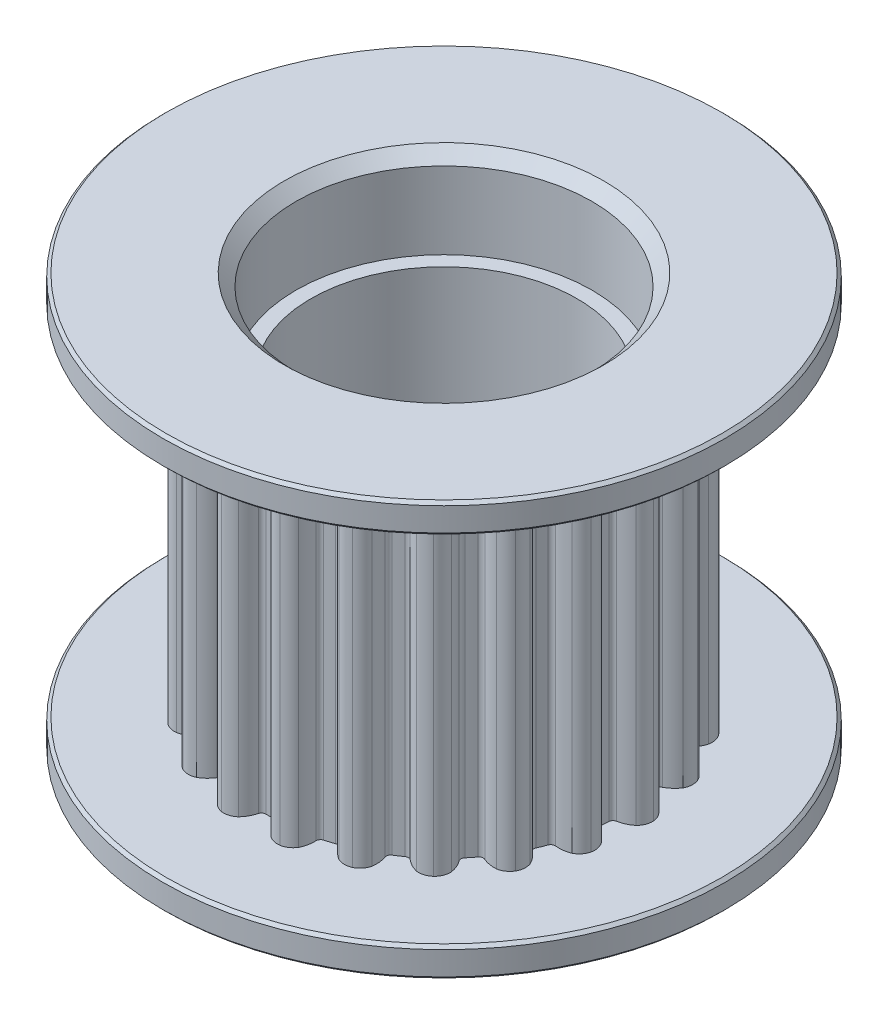
SolidWorks part; units mm, degrees
material "6061 Alloy"
ref_plane "Front Plane" through (0, 0, 0) normal (0, 0, 1) x (1, 0, 0)
ref_plane "Top Plane" through (0, 0, 0) normal (0, 1, 0) x (1, 0, 0)
ref_plane "Right Plane" through (0, 0, 0) normal (1, 0, 0) x (0, 0, -1)
sketch "Body Sketch" plane through (0, 0, 0) normal (0, 0, 1) x (1, 0, 0)
  line L0 (6.61, -6) -> (6.61, 6)
  line L1 (6.61, 6) -> (9.5, 6)
  line L2 (9.5, 6) -> (9.5, 7)
  line L3 (9.5, 7) -> (5, 7)
  line L4 (5, 7) -> (5, 4)
  line L5 (5, 4) -> (4.5, 4)
  line L6 (4.5, 4) -> (4.5, -4)
  line L7 (4.5, -4) -> (5, -4)
  line L8 (5, -4) -> (5, -7)
  line L9 (5, -7) -> (9.5, -7)
  line L10 (9.5, -7) -> (9.5, -6)
  line L11 (9.5, -6) -> (6.61, -6)
  line L12 (0, 0) -> (4.5, 0) construction
  line L13 (0, 7) -> (0, -7) construction
  dimension "BearingOD" = 10
  dimension "Height" = 14
  dimension "FlangeHeight" = 1
  dimension "BearingHeight" = 3
  dimension "BearingRestDiaControl" = 0.5
  dimension "RefBodyInnerDiameter" = 9
  dimension "FlangeDiaControl" = 4.5
  dimension "RefFlangeDia" = 19
  dimension "BeltPathDiaControl" = 1.61
  dimension "RefBeltPathDia" = 13.22
revolve "Body" add sketch "Body Sketch" angle 360 about L13
sketch "GT2 Profile Sketch" plane through (0, 0, 0) normal (0, 1, 0) x (1, 0, 0)
  line L1 (0, -6.61) -> (0, -5.86) construction
  line L2 (-0.9962, -6.5345) -> (-0.8832, -5.7931) construction
  line L3 (0, 0) -> (-0.8832, -5.7931) construction
  line L4 (0.9962, -6.5345) -> (0, 0) construction
  arc A3 (0.3083, -5.9702) -> (0.159, -5.8578) centre (0.1631, -6.0078) ccw
  arc A4 (-0.9962, -6.5345) -> (0.9962, -6.5345) centre (0, 0) ccw
  arc A5 (-0.3083, -5.9702) -> (-0.159, -5.8578) centre (-0.1631, -6.0078) cw
  arc A6 (-0.3083, -5.9702) -> (-0.5467, -6.4032) centre (-1.2763, -5.7193) cw
  circle A7 centre (0, 0) radius 6.61 construction
  arc A8 (-0.159, -5.8578) -> (0.159, -5.8578) centre (0, 0) ccw
  arc A9 (-0.5467, -6.4032) -> (-0.9962, -6.5345) centre (-0.9125, -5.9858) cw
  arc A10 (0.3083, -5.9702) -> (0.5467, -6.4032) centre (1.2763, -5.7193) ccw
  arc A11 (0.5467, -6.4032) -> (0.9962, -6.5345) centre (0.9125, -5.9858) ccw
  circle A12 centre (0, 0) radius 5.86 construction
  dimension "BottomRadius" = 0.15
  dimension "MidRadius" = 1
  dimension "TopRadius" = 0.555
  dimension "Height" = 0.75
  dimension "XDistMidRadius" = 0.4
  dimension "ArcLengthAngle" = 17.336
  dimension "ArcLength" = 2
sketch "Thru Bore Sketch" [suppressed] plane through (0, 0, 0) normal (0, 1, 0) x (1, 0, 0)
  circle A0 centre (0, 0) radius 4
  circle A2 centre (0, 0) radius 4 construction
extrude "Thru Bore" [suppressed] cut sketch "Thru Bore Sketch" against normal through all both and the other way through all
extrude "GT2 Profile" cut sketch "GT2 Profile Sketch" against normal up to surface and the other way up to surface up to face at (0, -6, 6.61) other way up to face at (0, 6, 9.5)
pattern_circular "GT2 Groove Circular Pattern" count 21 over 360 about axis through (0, 0, 0) along (0, 1, 0) of "GT2 Profile"
chamfer "Inner Chamfer" distance 0.4 angle 45 2 edges at (0, -7, 5) (0, 7, 5)
chamfer "Outer Chamfer" distance 0.1 angle 45 4 edges at (0, -7, 9.5) (0, -6, 9.5) (0, 6, 9.5) (0, 7, 9.5)
equation "\"NumTeeth@GT2 Groove Circular Pattern\"=int(360/\"ArcLengthAngle@GT2 Profile Sketch\")+1"
